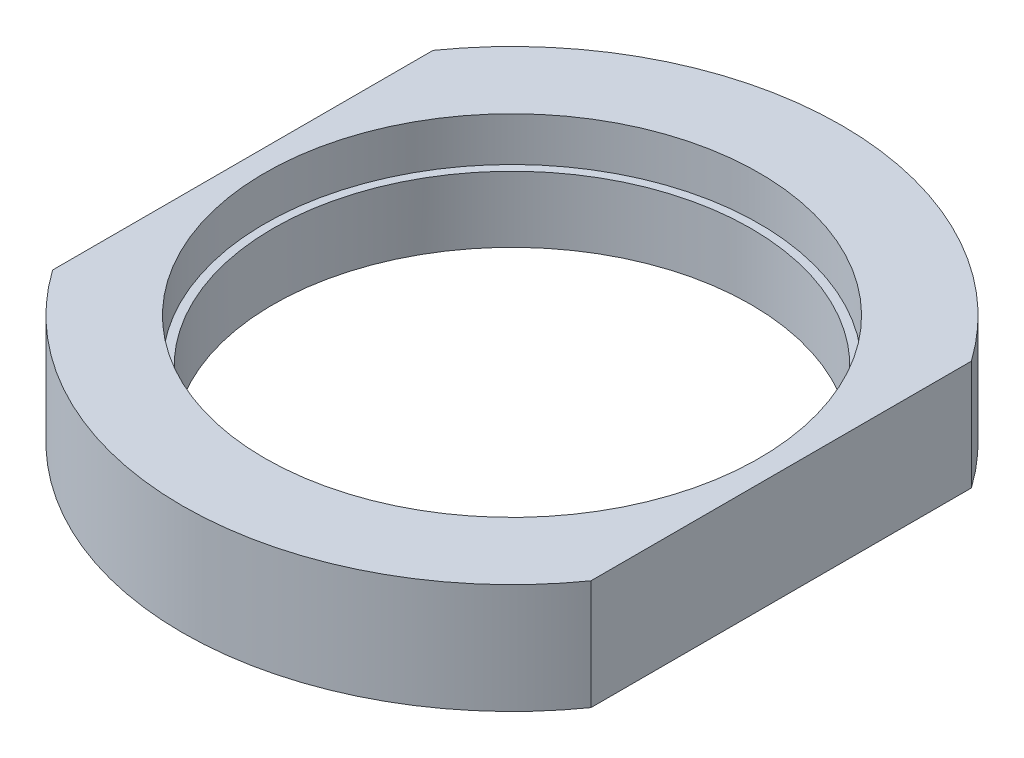
SolidWorks part; units mm, degrees
ref_plane "Front Plane" through (0, 0, 0) normal (0, 0, 1) x (1, 0, 0)
ref_plane "Top Plane" through (0, 0, 0) normal (0, 1, 0) x (1, 0, 0)
ref_plane "Right Plane" through (0, 0, 0) normal (1, 0, 0) x (0, 0, -1)
sketch "Sketch1" plane through (0, 0, 0) normal (0, 1, 0) x (1, 0, 0)
  line L0 (-49, 0) -> (49, 0) construction
  line L2 (-49, -34.6266) -> (-49, 34.6266)
  line L4 (49, -34.6266) -> (49, 34.6266)
  line L5 (-37.2422, -47.0427) -> (37.2422, 47.0427) construction
  line L6 (-37.2422, 47.0427) -> (37.2422, -47.0427) construction
  arc A0 (49, 34.6266) -> (-49, 34.6266) centre (0, 0) ccw
  arc A1 (-49, -34.6266) -> (49, -34.6266) centre (0, 0) ccw
  dimension "D1" = 60
  dimension "D2" = 98
extrude "Boss-Extrude1" add sketch "Sketch1" along normal blind 20
sketch "Sketch2" plane through (0, 0, 0) normal (0, -1, 0) x (1, 0, 0)
  circle A0 centre (0, 0) radius 43.5
  dimension "D1" = 87
extrude "Cut-Extrude2" cut sketch "Sketch2" against normal through all
sketch "Sketch3" plane through (0, 20, 0) normal (0, 1, 0) x (1, 0, 0)
  circle A0 centre (0, 0) radius 45
  dimension "D1" = 90
extrude "Cut-Extrude3" cut sketch "Sketch3" against normal blind 8
